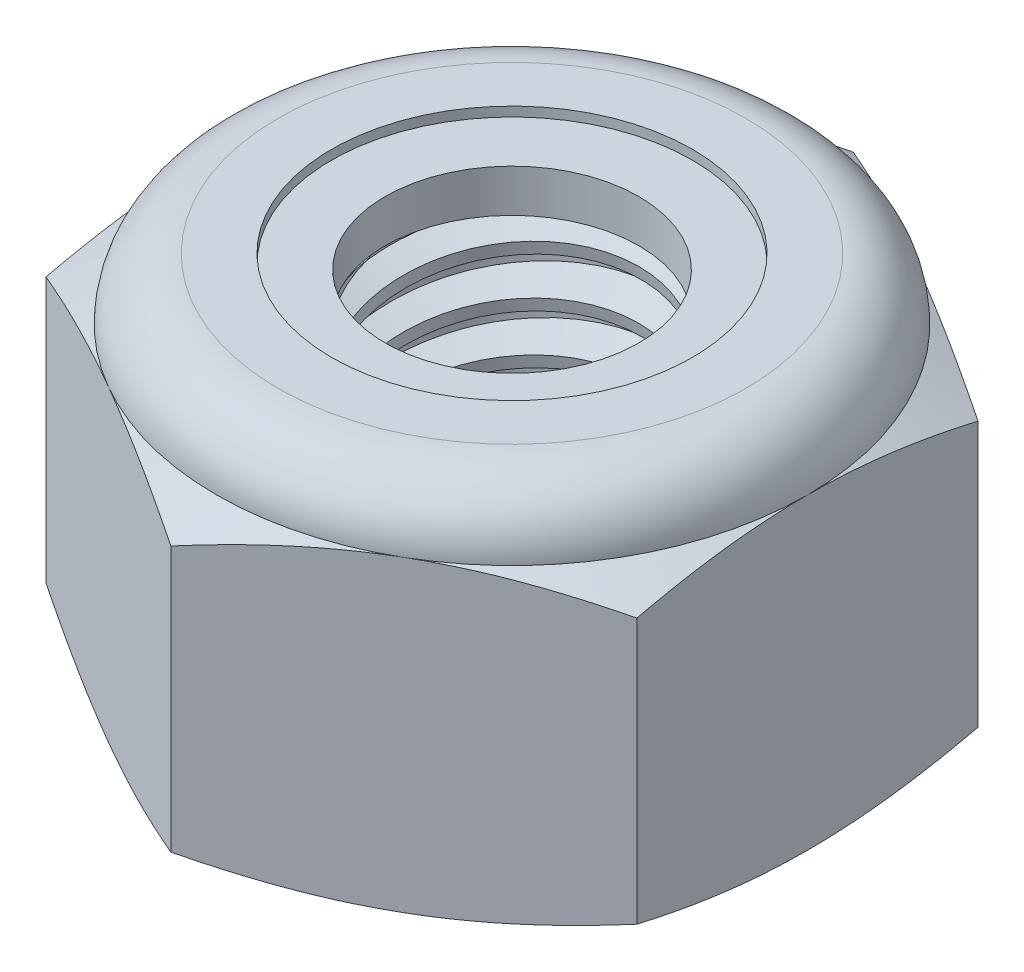
SolidWorks part; units mm, degrees
material "Alloy Steel"
ref_plane "Front" through (0, 0, 0) normal (0, 0, 1) x (1, 0, 0)
ref_plane "Top" through (0, 0, 0) normal (0, 1, 0) x (1, 0, 0)
ref_plane "Right" through (0, 0, 0) normal (1, 0, 0) x (0, 0, -1)
sketch "Sketch1" plane through (0, 0, 0) normal (0, 1, 0) x (1, 0, 0)
  line L1 (0, 5.4993) -> (-4.7625, 2.7496)
  line L2 (-4.7625, 2.7496) -> (-4.7625, -2.7496)
  line L3 (-4.7625, -2.7496) -> (0, -5.4993)
  line L4 (0, -5.4993) -> (4.7625, -2.7496)
  line L5 (4.7625, -2.7496) -> (4.7625, 2.7496)
  line L6 (4.7625, 2.7496) -> (0, 5.4993)
  circle A0 centre (0, 0) radius 4.7625 construction
  dimension "Hex Flats" = 9.525
extrude "Extrude1" add sketch "Sketch1" along normal blind 5.9531
sketch "Sketch2" plane through (0, 0, 0) normal (1, 0, 0) x (0, 0, -1)
  line L0 (-2.413, 0) -> (-2.413, 5.9531) construction
  line L1 (0, 0) -> (2.413, 0)
  line L2 (0, 0) -> (0, 5.9531)
  line L3 (0, 5.9531) -> (2.413, 5.9531)
  line L4 (2.413, 0) -> (2.413, 5.9531)
  line L5 (-2.7496, 5.9531) -> (2.7496, 5.9531) construction
  line L7 (0, -2.413) -> (0, 0) construction
  dimension "Thread Dia" = 4.826
revolve "Revolve1" add sketch "Sketch2" angle 360 about L7
sketch "Sketch3" plane through (0, 0, 0) normal (1, 0, 0) x (0, 0, -1)
  line L0 (2.413, 5.9531) -> (-2.413, 5.9531) construction
  line L1 (-2.413, 5.9531) -> (-2.413, 5.1594) construction
  line L2 (-2.413, 5.1594) -> (2.413, 5.9531) construction
  line L3 (2.413, 5.9531) -> (2.4291, 5.8552) construction
  line L4 (2.4291, 5.8552) -> (2.5418, 5.1699)
  line L5 (2.5418, 5.1699) -> (2.0776, 5.3449)
  line L6 (2.0776, 5.3449) -> (2.0454, 5.5407)
  line L7 (2.0454, 5.5407) -> (2.4291, 5.8552)
  line L8 (2.0615, 5.4428) -> (2.4855, 5.5126) construction
  line L9 (2.413, 5.9531) -> (2.413, 5.5006) construction
  line L10 (2.413, 5.5006) -> (-2.413, 4.7069) construction
  line L11 (-2.413, 4.7069) -> (-2.413, 5.1594) construction
  line L12 (-0.1397, 5.9531) -> (0.1397, 4.2544) construction
  line L13 (-2.413, 0) -> (-2.413, 5.9531) construction
  line L14 (0, 5.9531) -> (2.413, 5.9531) construction
  line L15 (2.413, 0) -> (2.413, 5.9531) construction
  point P13 (0, 5.1038)
  dimension "D1" = 0.0992
  dimension "D2" = 0.1984
  dimension "Thread Pitch" = 0.7937
  dimension "D4" = 60
  dimension "D5" = 0.7937
revolve "Cut-Revolve1" cut sketch "Sketch3" angle 360 about L12
pattern_linear "LPattern1" count 8 spacing 0.7937 along (0, -1, 0) count 2 spacing 0.7937 along (0, 1, 0) of "Cut-Revolve1"
sketch "Sketch4" plane through (0, 0, 0) normal (1, 0, 0) x (0, 0, -1)
  line L0 (0, 5.9531) -> (2.413, 5.9531)
  line L1 (2.413, 5.9531) -> (2.0454, 5.7817)
  line L2 (2.0454, 5.7817) -> (2.0454, 0.1714)
  line L3 (2.0454, 0.1714) -> (2.413, 0)
  line L4 (2.413, 0) -> (0, 0)
  line L5 (0, 0) -> (0, 5.9531)
  line L6 (2.413, 0) -> (2.413, 5.9531) construction
  line L7 (0, 5.9531) -> (2.413, 5.9531) construction
  line L8 (0, 0) -> (2.413, 0) construction
  line L9 (0, 0) -> (0, 5.9531) construction
  line L10 (0, 5.9531) -> (0, 6.3587) construction
  dimension "D1" = 25
revolve "Cut-Revolve2" cut sketch "Sketch4" angle 360 about L10
combine bodies "Combine1" operation type subtract main body 112 bodies to subtract 111
sketch "Sketch5" plane through (0, 0, 0) normal (1, 0, 0) x (0, 0, -1)
  line L0 (0, 0) -> (4.7625, 0)
  line L1 (4.7625, 0) -> (5.4993, 0.3436)
  line L2 (5.4993, 0.3436) -> (5.4993, 4.6174)
  line L3 (5.4993, 4.6174) -> (4.7625, 4.9609)
  line L4 (3.7703, 5.9531) -> (3.7703, 7.2231)
  line L5 (3.7703, 7.2231) -> (6.7693, 7.2231)
  line L6 (6.7693, 7.2231) -> (6.7693, -1.27)
  line L7 (6.7693, -1.27) -> (0, -1.27)
  line L8 (0, -1.27) -> (0, 0)
  line L9 (4.7625, 4.9609) -> (4.7625, 0) construction
  line L10 (0, 0) -> (2.413, 0) construction
  line L13 (5.4993, 2.4805) -> (6.7693, 2.4805) construction
  line L14 (5.4993, 5.9531) -> (5.4993, 0) construction
  line L15 (0, 0) -> (0, 7.2231) construction
  line L20 (0, 7.2231) -> (3.7703, 7.2231) construction
  line L22 (0, 5.9531) -> (2.413, 5.9531) construction
  arc A0 (4.7625, 4.9609) -> (3.7703, 5.9531) centre (3.7703, 4.9609) ccw
  dimension "D1" = 25
  dimension "D2" = 1.27
  dimension "D3" = 5.9531
  dimension "D4" = 0.9922
revolve "Cut-Revolve3" cut sketch "Sketch5" angle 360 about L15
sketch "Sketch6" plane through (0, 0, 0) normal (1, 0, 0) x (0, 0, -1)
  line L0 (0, 4.9609) -> (4.6101, 4.9609)
  line L1 (3.7703, 5.8007) -> (2.9079, 5.8007)
  line L2 (0, 7.2231) -> (0, 4.9609)
  line L3 (2.9079, 7.2231) -> (0, 7.2231)
  line L4 (0, 7.2231) -> (3.7703, 7.2231) construction
  line L5 (0, 0) -> (0, 7.2231) construction
  line L6 (0, 7.2231) -> (0, 44.323) construction
  line L7 (2.9079, 5.8007) -> (2.9079, 7.2231)
  line L8 (3.7703, 5.9531) -> (3.7703, 5.8007) construction
  line L9 (2.9079, 5.8007) -> (2.0454, 5.8007) construction
  line L10 (2.0454, 5.8007) -> (2.0454, 5.7817) construction
  arc A0 (4.6101, 4.9609) -> (3.7703, 5.8007) centre (3.7703, 4.9609) ccw
  arc A1 (4.7625, 4.9609) -> (3.7703, 5.9531) centre (3.7703, 4.9609) ccw construction
  dimension "D1" = 0.1524
revolve "Cut-Revolve4" cut sketch "Sketch6" angle 360 about L6
sketch "Sketch7" plane through (0, 0, 0) normal (1, 0, 0) x (0, 0, -1)
  line L0 (2.0454, 5.0371) -> (4.5301, 5.0371)
  line L1 (3.7703, 5.7245) -> (2.0454, 5.7245)
  line L2 (2.0454, 5.7245) -> (2.0454, 5.0371)
  line L3 (2.0454, 5.0371) -> (0, 5.0371) construction
  line L4 (0, 5.0371) -> (0, 5.7245) construction
  line L5 (0, 5.7245) -> (2.0454, 5.7245) construction
  line L6 (2.0454, 5.0371) -> (2.0454, 4.9609) construction
  line L7 (0, 4.9609) -> (4.6101, 4.9609) construction
  line L8 (3.7703, 5.7245) -> (3.7703, 5.8007) construction
  arc A0 (4.5301, 5.0371) -> (3.7703, 5.7245) centre (3.7703, 4.9609) ccw
  arc A2 (4.6101, 4.9609) -> (3.7703, 5.8007) centre (3.7703, 4.9609) ccw construction
  dimension "D1" = 0.0762
revolve "Revolve2" add sketch "Sketch7" angle 360 about L4
equation "\"D1@Sketch3\"=\"Thread Pitch@Sketch3\"/8"
equation "\"D2@Sketch3\"=\"Thread Pitch@Sketch3\"/4"
equation "\"D5@Sketch3\"=\"Thread Pitch@Sketch3\""
equation "\"D4@LPattern1\"=\"Thread Pitch@Sketch3\""
equation "\"D3@LPattern1\"=\"Thread Pitch@Sketch3\""
equation "\"D1@LPattern1\"=\"Height@Extrude1\"/\"Thread Pitch@Sketch3\""
equation "\"D4@Sketch5\"=\"Height@Extrude1\"/6"
